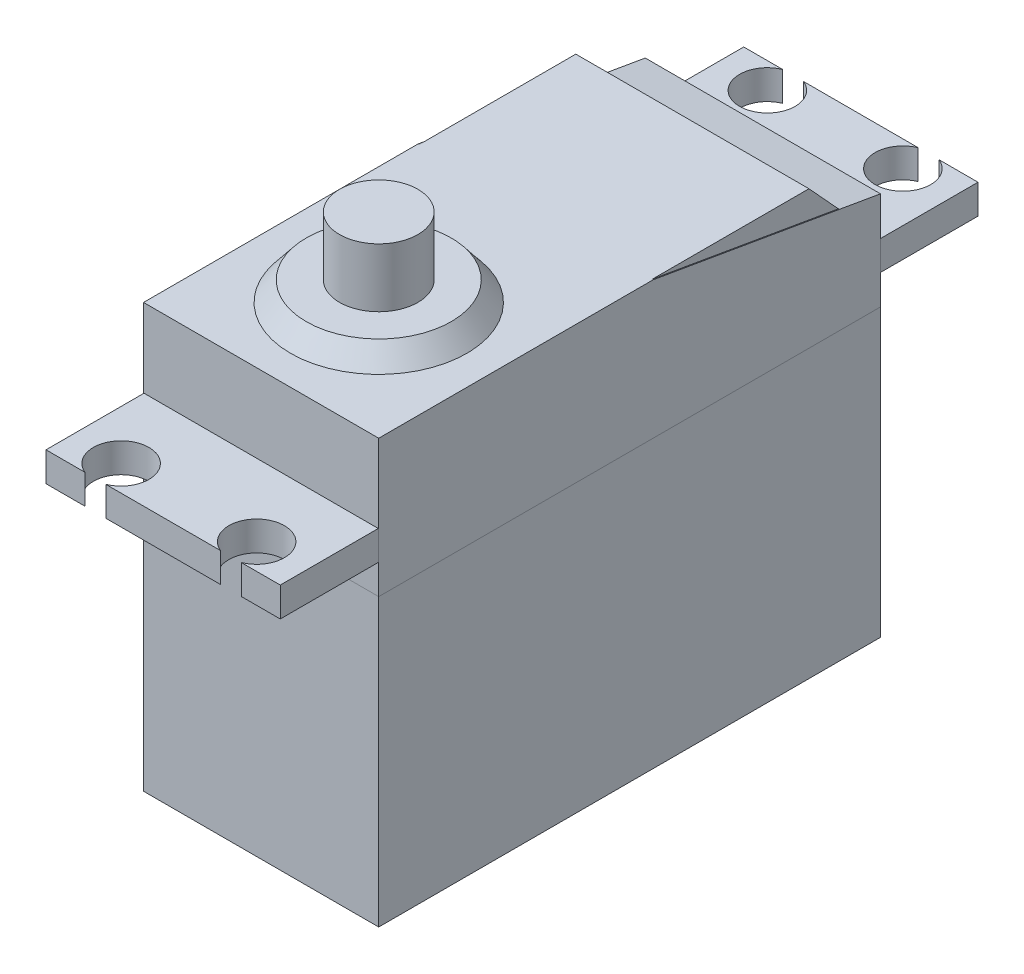
SolidWorks part; units mm, degrees
ref_plane "Front Plane" through (0, 0, 0) normal (0, 0, 1) x (1, 0, 0)
ref_plane "Top Plane" through (0, 0, 0) normal (0, 1, 0) x (1, 0, 0)
ref_plane "Right Plane" through (0, 0, 0) normal (1, 0, 0) x (0, 0, -1)
sketch "Sketch1" plane through (0, 0, 0) normal (0, 1, 0) x (1, 0, 0)
  line L1 (-9.525, -19.05) -> (9.525, -19.05)
  line L2 (-9.525, -19.05) -> (-9.525, 21.59)
  line L3 (-9.525, 21.59) -> (9.525, 21.59)
  line L4 (9.525, -19.05) -> (9.525, 21.59)
extrude "Boss-Extrude1" add sketch "Sketch1" along normal blind 23.8125
chamfer "Chamfer1" distance 0.635 angle 45 4 edges at (0, 0, 19.05) (9.525, 0, -1.27) (0, 0, -21.59) (-9.525, 0, -1.27)
sketch "Sketch2" plane through (0, 0, -21.59) normal (0, 0, -1) x (-1, 0, 0)
  line L0 (-9.525, 0.635) -> (9.525, 0.635) construction
  line L1 (-3.175, 3.81) -> (3.175, 3.81)
  line L2 (-3.175, 3.81) -> (-3.175, 0.635)
  line L3 (-3.175, 0.635) -> (3.175, 0.635)
  line L4 (3.175, 3.81) -> (3.175, 0.635)
  line L5 (-3.175, 3.81) -> (3.175, 0.635) construction
  line L6 (-3.175, 0.635) -> (3.175, 3.81) construction
  point P0 (0, 2.2225)
  dimension "D1" = 3.175
  dimension "D2" = 6.35
ref_plane "Plane1" through (0, 0, -26.67) normal (0, 0, -1) x (-1, 0, 0)
sketch "Sketch3" plane through (0, 0, -26.67) normal (0, 0, -1) x (-1, 0, 0)
  line L8 (2.3812, 3.0162) -> (-2.3813, 3.0162)
  line L9 (2.3812, 1.4287) -> (2.3812, 3.0162)
  line L10 (-2.3813, 1.4287) -> (2.3812, 1.4287)
  line L11 (-2.3813, 3.0162) -> (-2.3813, 1.4287)
  line L12 (2.3812, 3.0162) -> (-2.3813, 3.0162)
  line L13 (2.3812, 1.4287) -> (2.3812, 3.0162)
  line L14 (-2.3813, 1.4287) -> (2.3812, 1.4287)
  line L15 (-2.3813, 3.0162) -> (-2.3813, 1.4287)
  dimension "D1" = 0.7937
extrude "Boss-Extrude3" add sketch "Sketch2" along normal blind 1.27
sketch "Sketch4" plane through (0, 0, -22.86) normal (0, 0, -1) x (-1, 0, 0)
  line L0 (2.9972, 3.6322) -> (-2.9972, 3.6322)
  line L1 (-2.9972, 3.6322) -> (-2.9972, 0.8128)
  line L2 (-2.9972, 0.8128) -> (2.9972, 0.8128)
  line L3 (2.9972, 0.8128) -> (2.9972, 3.6322)
loft "Loft1" add profiles "Sketch4", "Sketch3"
sketch "Sketch6" plane through (0, 23.8125, 0) normal (0, 1, 0) x (1, 0, 0)
  line L0 (9.525, 21.59) -> (-9.525, 21.59) construction
  line L1 (-9.525, 21.59) -> (-9.525, -19.05) construction
  line L2 (9.525, -19.05) -> (9.525, 21.59) construction
  line L3 (-9.525, -19.05) -> (9.525, -19.05) construction
  line L4 (9.525, 21.59) -> (-9.525, 21.59)
  line L5 (-9.525, 21.59) -> (-9.525, -19.05)
  line L6 (9.525, -19.05) -> (9.525, 21.59)
  line L7 (-9.525, -19.05) -> (9.525, -19.05)
extrude "Boss-Extrude6" add sketch "Sketch6" along normal blind 11.1125 separate body
sketch "Sketch8" plane through (9.525, 0, 0) normal (1, 0, 0) x (0, 0, -1)
  line L0 (21.59, 31.75) -> (3.175, 34.925)
  line L1 (21.59, 34.925) -> (21.59, 23.8125) construction
  line L2 (-19.05, 34.925) -> (21.59, 34.925) construction
  line L3 (-19.05, 23.8125) -> (21.59, 23.8125) construction
  line L4 (-19.05, 34.925) -> (-19.05, 23.8125) construction
  line L5 (3.175, 34.925) -> (21.59, 34.925)
  line L6 (21.59, 34.925) -> (21.59, 31.75)
  dimension "D1" = 7.9375
  dimension "D2" = 22.225
extrude "Cut-Extrude1" cut sketch "Sketch8" against normal through all
ref_plane "Plane2" through (9.4488, 0, 0) normal (1, 0, 0) x (0, 0, -1)
sketch "Sketch11" plane through (9.4488, 0, 0) normal (1, 0, 0) x (0, 0, -1)
  line L0 (3.175, 34.925) -> (15.875, 34.925)
  line L1 (15.875, 34.925) -> (18.2562, 32.3248)
  line L2 (3.175, 34.925) -> (21.59, 31.75) construction
  line L3 (18.2562, 32.3248) -> (3.175, 34.925)
  dimension "D1" = 12.7
  dimension "D2" = 15.0812
extrude "Boss-Extrude7" add sketch "Sketch11" against normal blind 18.8849
sketch "Sketch12" plane through (0, 34.925, 0) normal (0, 1, 0) x (1, 0, 0)
  line L0 (-9.525, -19.05) -> (9.525, -19.05) construction
  circle A0 centre (0, -9.525) radius 7.1438
  dimension "D2" = 14.2875
  dimension "D1" = 9.525
ref_plane "Plane3" through (0, 36.5125, 0) normal (0, 1, 0) x (-1, 0, 0)
sketch "Sketch13" plane through (0, 36.5125, 0) normal (0, 1, 0) x (-1, 0, 0)
  circle A4 centre (0, 9.525) radius 5.8738
  circle A5 centre (0, 9.525) radius 5.8738
  dimension "D1" = 1.27
loft "Loft5" add profiles "Sketch13", "Sketch12"
sketch "Sketch14" plane through (0, 36.5125, 0) normal (0, 1, 0) x (1, 0, 0)
  circle A0 centre (0, -9.525) radius 3.175
extrude "Boss-Extrude8" add sketch "Sketch14" along normal blind 4.7625
sketch "Sketch15" plane through (0, 0, -21.59) normal (0, 0, -1) x (-1, 0, 0)
  line L0 (-9.525, 23.8125) -> (9.525, 23.8125) construction
  line L1 (-9.4877, 26.1938) -> (9.4877, 26.1938)
  line L2 (-9.4877, 26.1938) -> (-9.4877, 28.575)
  line L3 (-9.4877, 28.575) -> (9.4877, 28.575)
  line L4 (9.4877, 26.1938) -> (9.4877, 28.575)
  line L5 (-9.4877, 26.1938) -> (9.4877, 28.575) construction
  line L6 (-9.4877, 28.575) -> (9.4877, 26.1938) construction
  point P0 (0, 27.3844)
  dimension "D1" = 2.3813
  dimension "D2" = 2.3813
extrude "Boss-Extrude9" add sketch "Sketch15" along normal blind 7.9375
sketch "Sketch16" plane through (0, 0, 19.05) normal (0, 0, 1) x (1, 0, 0)
  line L0 (-9.4877, 26.1938) -> (-9.4877, 28.575) construction
  line L1 (-9.4877, 28.575) -> (9.4877, 28.575) construction
  line L2 (9.4877, 26.1938) -> (-9.4877, 26.1938) construction
  line L3 (9.4877, 28.575) -> (9.4877, 26.1938) construction
  line L4 (-9.4877, 26.1938) -> (-9.4877, 28.575)
  line L5 (-9.4877, 28.575) -> (9.4877, 28.575)
  line L6 (9.4877, 26.1938) -> (-9.4877, 26.1938)
  line L7 (9.4877, 28.575) -> (9.4877, 26.1938)
extrude "Boss-Extrude10" add sketch "Sketch16" along normal blind 7.9375
sketch "Sketch17" plane through (0, 28.575, 0) normal (0, 1, 0) x (1, 0, 0)
  line L3 (9.4877, -26.9875) -> (9.4877, -19.05) construction
  line L5 (0, -9.525) -> (0, -41.0916) construction
  line L6 (-18.894, 1.27) -> (49.5404, 1.27) construction
  line L7 (-9.4877, 21.59) -> (9.4877, 21.59) construction
  line L8 (9.4877, -19.05) -> (-9.4877, -19.05) construction
  circle A0 centre (5.4877, -24.9012) radius 2.25
  circle A1 centre (-5.4877, -24.9012) radius 2.25
  circle A2 centre (-5.4877, 27.4412) radius 2.25
  circle A3 centre (5.4877, 27.4412) radius 2.25
  dimension "D3" = 20.32
  dimension "D1" = 4
  dimension "D2" = 20.32
extrude "Cut-Extrude2" cut sketch "Sketch17" against normal through all
